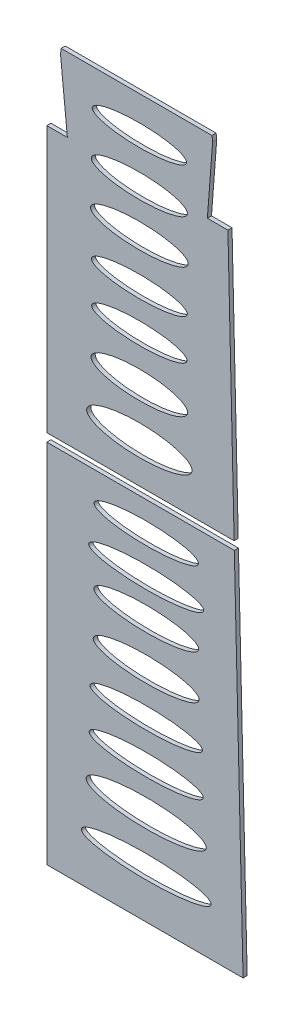
SolidWorks part; units mm, degrees
ref_plane "前视基准面" through (0, 0, 0) normal (0, 0, 1) x (1, 0, 0)
ref_plane "上视基准面" through (0, 0, 0) normal (0, 1, 0) x (1, 0, 0)
ref_plane "右视基准面" through (0, 0, 0) normal (1, 0, 0) x (0, 0, -1)
sketch "Model" plane through (0, 0, 0) normal (0, 0, 1) x (1, 0, 0)
  line L0 (838.8123, 453.3655) -> (884.3613, 453.3655)
  line L1 (842.2992, 536.0298) -> (878.9752, 536.0298)
  line L2 (884.3613, 453.3655) -> (882.8523, 518.0353)
  line L3 (838.8123, 453.3655) -> (838.8126, 518.0298)
  line L4 (838.8126, 518.0298) -> (843.8126, 518.0298)
  line L5 (843.8126, 518.0298) -> (842.1425, 534.7313)
  line L6 (882.8523, 518.0353) -> (877.8523, 518.0353)
  line L7 (877.8523, 518.0353) -> (879.138, 534.8004)
  line L8 (838.8121, 362.3794) -> (838.8123, 451.3655)
  line L9 (838.8121, 362.3794) -> (886.5357, 362.3794)
  line L10 (884.4091, 451.3655) -> (838.8123, 451.3655)
  line L11 (886.5357, 362.3794) -> (884.4091, 451.3655)
  line L12 (842.2992, 536.0298) -> (842.1425, 534.7313)
  line L13 (878.9752, 536.0298) -> (879.138, 534.8004)
  ellipse E0 centre (861.313, 463.0347) end of major axis (874.1238, 463.0347) minor radius 3.6769
  ellipse E1 centre (861.313, 474.6966) end of major axis (873.0485, 474.6966) minor radius 3.3442
  ellipse E2 centre (861.313, 485.5761) end of major axis (872.9006, 485.5761) minor radius 2.6204
  ellipse E3 centre (861.313, 495.4071) end of major axis (872.9783, 495.4071) minor radius 2.5959
  ellipse E4 centre (861.313, 506.0969) end of major axis (873.2048, 506.0969) minor radius 3.0159
  ellipse E5 centre (861.313, 516.5922) end of major axis (873.0065, 516.5922) minor radius 2.9095
  ellipse E6 centre (861.313, 527.2614) end of major axis (872.7806, 527.2614) minor radius 2.6136
  ellipse E7 centre (862.9757, 374.0243) end of major axis (878.7638, 374.0243) minor radius 2.7983
  ellipse E8 centre (862.9757, 385.3208) end of major axis (877.5908, 385.3208) minor radius 3.3442
  ellipse E9 centre (862.9757, 395.5217) end of major axis (876.8496, 395.5217) minor radius 2.6204
  ellipse E10 centre (862.9757, 405.3772) end of major axis (876.6502, 405.3772) minor radius 2.5959
  ellipse E11 centre (862.9757, 415.647) end of major axis (875.8565, 415.647) minor radius 3.0159
  ellipse E12 centre (862.9757, 426.2488) end of major axis (875.7238, 426.2488) minor radius 2.9095
  ellipse E13 centre (862.9757, 434.9952) end of major axis (876.9588, 434.9952) minor radius 2.6136
  ellipse E14 centre (862.9757, 444.2489) end of major axis (875.6637, 444.2489) minor radius 2.6136
extrude "凸台-拉伸1" add sketch "Model" along normal blind 1
